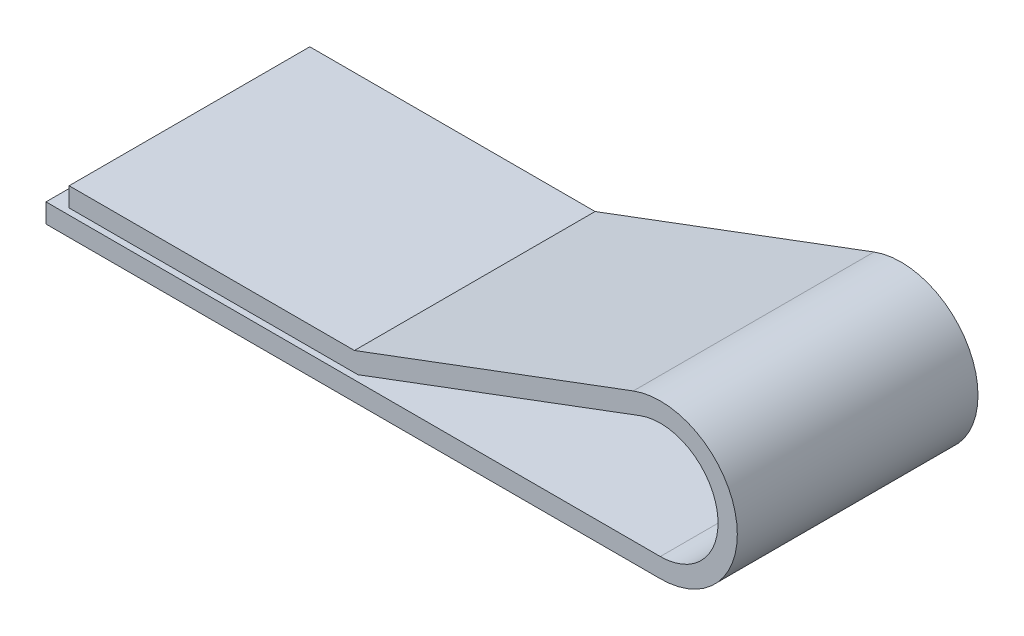
SolidWorks part; units mm, degrees
material "Nylon 101"
ref_plane "Front Plane" through (0, 0, 0) normal (0, 0, 1) x (1, 0, 0)
ref_plane "Top Plane" through (0, 0, 0) normal (0, 1, 0) x (1, 0, 0)
ref_plane "Right Plane" through (0, 0, 0) normal (1, 0, 0) x (0, 0, -1)
sketch "Sketch1" plane through (0, 0, 0) normal (0, 0, 1) x (1, 0, 0)
  line L0 (-63.8096, 0) -> (0, 0)
  line L1 (-2.1033, 11.6193) -> (-31.4091, 0.65)
  line L2 (-31.4091, 0.65) -> (-61.4091, 0.65)
  arc A0 (0, 0) -> (-2.1033, 11.6193) centre (0, 6) ccw
  point P0 (-63.8096, 0)
  dimension "D1" = 6
  dimension "D4" = 30
  dimension "D5" = 0.65
  dimension "D7" = 31.4091
extrude "Extrude-Thin1" add sketch "Sketch1" along normal mid plane 25 thin
equation "\"Length1\"= 20.78"
equation "\"Length2\"=50"
equation "\"Length3\"=211.949"
equation "\"Thicknes\"=2"
equation "\"D5@Extrude-Thin1\"=\"Thicknes\""
